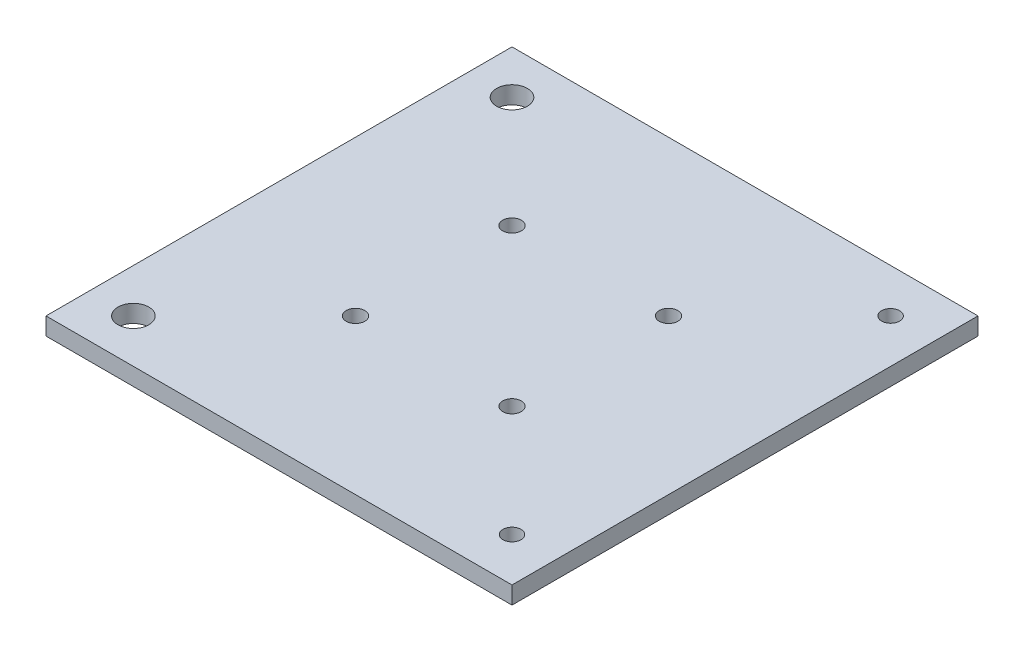
SolidWorks part; units mm, degrees
ref_plane "前视基准面" through (0, 0, 0) normal (0, 0, 1) x (1, 0, 0)
ref_plane "上视基准面" through (0, 0, 0) normal (0, 1, 0) x (1, 0, 0)
ref_plane "右视基准面" through (0, 0, 0) normal (1, 0, 0) x (0, 0, -1)
other "Configuration Table"
sketch "草图1" plane through (0, 0, 0) normal (0, 1, 0) x (1, 0, 0)
  line L1 (-40, -40) -> (40, -40)
  line L2 (-40, -40) -> (-40, 40)
  line L3 (-40, 40) -> (40, 40)
  line L4 (40, -40) -> (40, 40)
  line L5 (-40, -40) -> (40, 40) construction
  line L6 (-40, 40) -> (40, -40) construction
  line L7 (-32.5, -32.5) -> (32.5, -32.5)
  line L8 (-32.5, -32.5) -> (-32.5, 32.5)
  line L9 (-32.5, 32.5) -> (32.5, 32.5)
  line L10 (32.5, -32.5) -> (32.5, 32.5)
  line L11 (-32.5, -32.5) -> (32.5, 32.5) construction
  line L12 (-32.5, 32.5) -> (32.5, -32.5) construction
  circle A0 centre (-32.5, 32.5) radius 2.65
  circle A1 centre (-32.5, -32.5) radius 2.65
  circle A2 centre (32.5, 32.5) radius 1.55
  circle A3 centre (32.5, -32.5) radius 1.55
  point P0 (0, 0)
  point P6 (0, 0)
  dimension "D4" = 5.3
  dimension "D5" = 5.3
  dimension "D6" = 3.1
  dimension "D7" = 3.1
  dimension "D1" = 80
  dimension "D2" = 80
  dimension "D3" = 65
extrude "凸台-拉伸1" add sketch "草图1" along normal blind 4 contours L1 L4 L3 L2 A3 L7 A1 L8 A0 L9 A2 L10 | A3 L10 A2 L9 A0 L8 A1 L7
sketch "草图2" plane through (0, 4, 0) normal (0, 1, 0) x (1, 0, 0)
  line L0 (-1000, 0) -> (49000, 0) construction
  line L1 (0, 0) -> (35355.3391, 35355.3391) construction
  circle A0 centre (0, 0) radius 19
  circle A1 centre (13.435, 13.435) radius 1.6
  circle A2 centre (13.435, -13.435) radius 1.6
  circle A3 centre (-13.435, -13.435) radius 1.6
  circle A4 centre (-13.435, 13.435) radius 1.6
  point P18 (0, 0)
  dimension "D1" = 38
  dimension "D3" = 3.2
  dimension "D2" = 45
  dimension "D4" = 4
extrude "切除-拉伸1" cut sketch "草图2" against normal through all contours A4 | A3 | A2 | A1
sketch "草图3" plane through (0, 0, 0) normal (0, -1, 0) x (1, 0, 0)
  line L1 (-47.8552, 44.4983) -> (66.5914, 44.4983)
  line L2 (-47.8552, 44.4983) -> (-47.8552, -48.4017)
  line L3 (-47.8552, -48.4017) -> (66.5914, -48.4017)
  line L4 (66.5914, 44.4983) -> (66.5914, -48.4017)
extrude "切除-拉伸2" cut sketch "草图3" against normal blind 1
